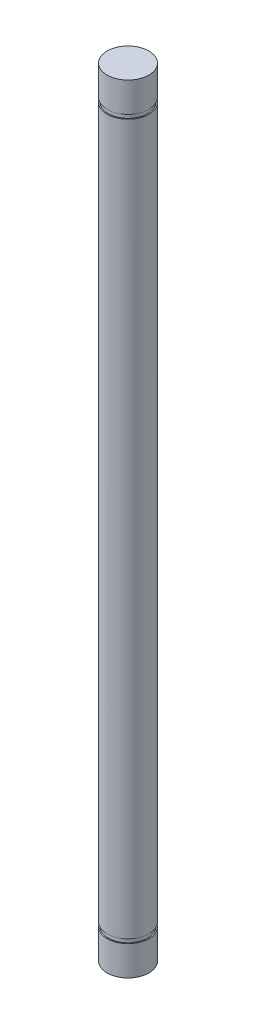
SolidWorks part; units mm, degrees
ref_plane "前视" through (0, 0, 0) normal (0, 0, 1) x (1, 0, 0)
ref_plane "上视" through (0, 0, 0) normal (0, 1, 0) x (1, 0, 0)
ref_plane "右视" through (0, 0, 0) normal (1, 0, 0) x (0, 0, -1)
sketch "草图1" plane through (0, 0, 0) normal (0, 1, 0) x (1, 0, 0)
  circle A0 centre (0, 0) radius 4
  dimension "D1" = 8
extrude "凸台-拉伸1" add sketch "草图1" along normal mid plane 149
sketch "草图3" plane through (0, 0, 0) normal (1, 0, 0) x (0, 0, -1)
  line L0 (0, 74.5) -> (0, -74.5) construction
  line L1 (3.8, 68.8) -> (8.8, 68.8)
  line L2 (3.8, 68.8) -> (3.8, 68)
  line L3 (3.8, 68) -> (8.8, 68)
  line L4 (8.8, 68.8) -> (8.8, 68)
  line L5 (3.8, 68.8) -> (8.8, 68) construction
  line L6 (3.8, 68) -> (8.8, 68.8) construction
  point P0 (6.3, 68.4)
  dimension "D1" = 68
  dimension "D2" = 0.8
  dimension "D3" = 3.8
  dimension "D4" = 5
revolve "切除-旋转1" cut sketch "草图3" angle 360 about axis through (0, 74.5, 0) along (0, -1, 0)
ref_plane "基准面1" through (0, 0, 0) normal (0, 1, 0) x (1, 0, 0)
mirror "镜向1" about plane through (0, 0, 0) normal (0, 1, 0) of "切除-旋转1"
